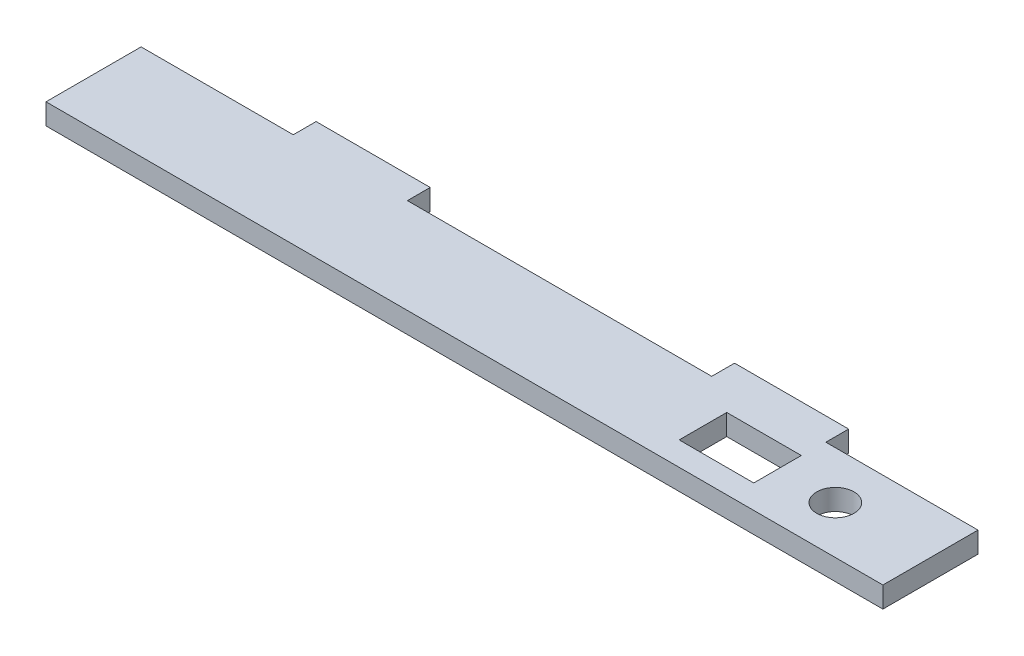
SolidWorks part; units mm, degrees
ref_plane "Front Plane" through (0, 0, 0) normal (0, 0, 1) x (1, 0, 0)
ref_plane "Top Plane" through (0, 0, 0) normal (0, 1, 0) x (1, 0, 0)
ref_plane "Right Plane" through (0, 0, 0) normal (1, 0, 0) x (0, 0, -1)
sketch "Sketch1" plane through (0, 0, 0) normal (0, 1, 0) x (1, 0, 0)
  line L0 (0, -55) -> (0, 55) construction
  line L1 (-110, -12.5) -> (110, -12.5)
  line L2 (-110, -12.5) -> (-110, 12.5)
  line L3 (-110, 12.5) -> (110, 12.5)
  line L4 (110, -12.5) -> (110, 12.5)
  line L5 (-110, -12.5) -> (110, 12.5) construction
  line L6 (-110, 12.5) -> (110, -12.5) construction
  line L7 (-70, 12.5) -> (-40, 12.5)
  line L8 (-70, 12.5) -> (-70, 18.5)
  line L9 (-70, 18.5) -> (-40, 18.5)
  line L10 (-40, 12.5) -> (-40, 18.5)
  line L11 (40, 12.5) -> (40, 18.5)
  line L12 (70, 12.5) -> (70, 18.5)
  line L13 (70, 18.5) -> (40, 18.5)
  point P0 (0, 0)
  dimension "D1" = 25
  dimension "D2" = 220
  dimension "D3" = 40
  dimension "D4" = 6
  dimension "D5" = 30
extrude "Boss-Extrude1" add sketch "Sketch1" along normal blind 5.5 contours L3 L10 L9 L8 | L1 L4 L3 L2 | L12 L13 L11 L3
sketch "Sketch2" plane through (0, 5.5, 0) normal (0, 1, 0) x (1, 0, 0)
  line L0 (-3.025, 0) -> (3.025, 0) construction
  line L1 (50.2, -6.25) -> (69.8, -6.25)
  line L2 (50.2, -6.25) -> (50.2, 6.25)
  line L3 (50.2, 6.25) -> (69.8, 6.25)
  line L4 (69.8, -6.25) -> (69.8, 6.25)
  line L5 (50.2, -6.25) -> (69.8, 6.25) construction
  line L6 (50.2, 6.25) -> (69.8, -6.25) construction
  line L7 (110, -12.5) -> (110, 12.5) construction
  circle A0 centre (85, 0) radius 4.9
  point P0 (60, 0)
  point P9 (58.9174, 0)
  point P10 (89.5799, 0)
  dimension "D1" = 9.8
  dimension "D2" = 25
  dimension "D3" = 25
  dimension "D4" = 12.5
  dimension "D5" = 19.6
extrude "Cut-Extrude1" cut sketch "Sketch2" against normal through all
